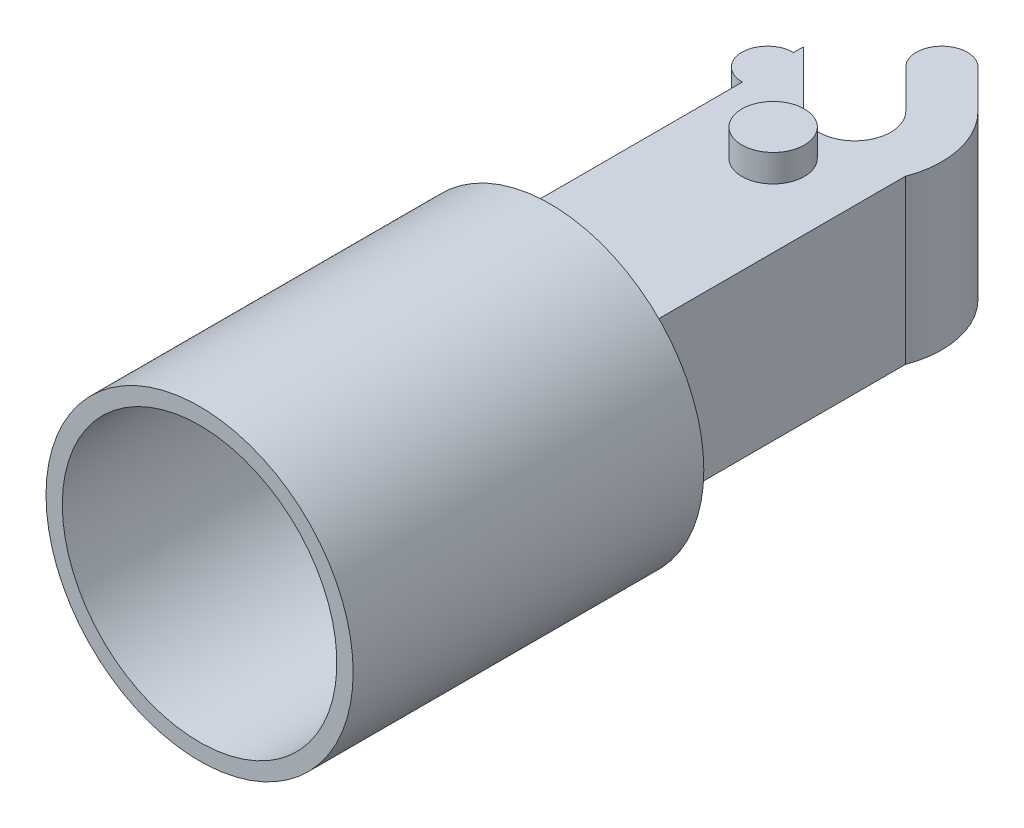
SolidWorks part; units mm, degrees
material "6063-T5"
ref_plane "Front Plane" through (0, 0, 0) normal (0, 0, 1) x (1, 0, 0)
ref_plane "Top Plane" through (0, 0, 0) normal (0, 1, 0) x (1, 0, 0)
ref_plane "Right Plane" through (0, 0, 0) normal (1, 0, 0) x (0, 0, -1)
sketch "Sketch1" plane through (0, 0, 0) normal (0, 1, 0) x (1, 0, 0)
  circle A0 centre (0, 0) radius 2.875
  dimension "D1" = 5.75
extrude "Boss-Extrude1" add sketch "Sketch1" along normal blind 20
ref_plane "Plane4" through (0, 2.5, 0) normal (0, -1, 0) x (-1, 0, 0)
sketch "Sketch2" plane through (0, 2.5, 0) normal (0, -1, 0) x (-1, 0, 0)
  line L0 (-7.5, 0) -> (-7.5, 10)
  line L1 (7.5, 10) -> (7.5, 0)
  line L2 (-4, 0) -> (-4, 10)
  line L3 (4, 0) -> (4, 10)
  line L4 (-7.5, 10) -> (-4, 10)
  line L5 (4, 10) -> (7.5, 10)
  line L6 (7.5, 0) -> (4, 0)
  circle A0 centre (0, 0) radius 7.5
  circle A1 centre (0, 0) radius 4
  circle A2 centre (-5.75, 10) radius 1.75
  circle A3 centre (5.75, 10) radius 1.75
  circle A4 centre (0, 0) radius 2.875
  circle A5 centre (0, 7.5) radius 4
  dimension "D1" = 15
  dimension "D3" = 10
  dimension "D4" = 5.75
  dimension "D2" = 10
extrude "Boss-Extrude2" add sketch "Sketch2" against normal blind 14.99
sketch "Sketch3" plane through (0, 2.5, 0) normal (0, -1, 0) x (-1, 0, 0)
  line L0 (7.5, 0) -> (7.5, -20.5)
  line L1 (-7.5, 0) -> (-7.5, -20.5)
  line L2 (-7.5, -20.5) -> (7.5, -20.5)
  arc A0 (7.5, 0) -> (-7.5, 0) centre (0, 0) cw
  dimension "D1" = 20.5
  dimension "D2" = 20.5
extrude "Boss-Extrude3" add sketch "Sketch3" against normal up to surface (14.99 mm away) up to face at (0, 17.49, -5.875)
sketch "Sketch4" plane through (0, 0, 20.5) normal (0, 0, 1) x (1, 0, 0)
  line L0 (-7.5, 9.995) -> (7.5, 9.995)
  line L1 (-7.5, 17.49) -> (-7.5, 2.5) construction
  line L2 (7.5, 17.49) -> (7.5, 2.5) construction
  circle A0 centre (0, 9.995) radius 14.125
  line M1 (7.5, 17.49) -> (-7.5, 17.49)
  line M2 (-7.5, 17.49) -> (-7.5, 2.5)
  line M3 (-7.5, 2.5) -> (7.5, 2.5)
  line M4 (7.5, 2.5) -> (7.5, 17.49)
  dimension "D1" = 28.25
extrude "Boss-Extrude4" add sketch "Sketch4" along normal blind 6.25 contours A0 M1 M4 M3 M2 | L0 M2 M4 M1 | L0 M2 M3 M4
sketch "Sketch5" plane through (0, 0, 26.75) normal (0, 0, 1) x (1, 0, 0)
  circle A0 centre (0, 9.995) radius 14.125
  circle A1 centre (0, 9.995) radius 12.625
  dimension "D1" = 28.25
  dimension "D2" = 25.25
extrude "Boss-Extrude5" add sketch "Sketch5" along normal blind 26
sketch "Sketch6" plane through (0, 2.5, 0) normal (0, -1, 0) x (-1, 0, 0)
  line L0 (-4.01, 11.51) -> (-5.671, 13.171)
  line L1 (-8.02, 7.5) -> (0, 15.52)
  line L2 (0, 15.52) -> (8.02, 7.5)
  line L3 (8.02, 7.5) -> (0, -0.52)
  line L4 (0, -0.52) -> (-8.02, 7.5)
  line L5 (-5.671, 13.171) -> (-2.1354, 16.7065)
  line L6 (-4.01, 11.51) -> (-2.349, 9.849)
  line L7 (-2.349, 9.849) -> (1.1865, 13.3845)
  line L8 (-2.1354, 16.7065) -> (1.1865, 13.3845)
  line L9 (4.01, 3.49) -> (5.671, 1.829)
  line L10 (5.671, 1.829) -> (9.2065, 5.3646)
  line L11 (4.01, 3.49) -> (2.349, 5.151)
  line L12 (2.349, 5.151) -> (5.8845, 8.6865)
  line L13 (5.8845, 8.6865) -> (9.2065, 5.3646)
  circle A1 centre (0, 7.5) radius 8.02
  circle A2 centre (-4.01, 11.51) radius 2.349
  circle A4 centre (4.01, 3.49) radius 2.349
  circle A5 centre (0, 7.5) radius 3.322
  circle A6 centre (-0.4745, 15.0455) radius 2.349
  circle A8 centre (7.5455, 7.0255) radius 2.35
  arc M15 (4, 7.5) -> (-4, 7.5) centre (0, 7.5) cw
  line M16 (-4, 7.5) -> (-4, 10)
  arc M17 (-4, 10) -> (-7.5, 10) centre (-5.75, 10) ccw
  line M18 (-7.5, 10) -> (-7.5, -20.5)
  line M20 (7.5, -20.5) -> (7.5, 10)
  circle M22 centre (0, 0) radius 2.875
  dimension "D5" = 4.7
  dimension "D1" = 5
  dimension "D2" = 5
  dimension "D3" = 5
  dimension "D4" = 5
extrude "Boss-Extrude8" add sketch "Sketch6" against normal up to surface (14.99 mm away) contours A6 L5 A1 | A6 A1 A2 L1 | A6 L1 A2 L7 | A2 A1 M17 | A2 L1 M17 M18 | A4 A2 L1 L4 L3 M15 M16 M18 M22 | A5 A2 A4 M16 M15 | A1 L1 M17 M18 | L4 L1 M18 | L4 A1 M18 | A1 L4 M18 M22 | A8 L12 A4 L3 M15 | A8 L3 A4 A1 M20 | A4 L3 A1 M22 | L4 L3 M22 | L3 A1 M22 | A1 L4 M22 | A4 L12 M15
sketch "Sketch7" plane through (0, 2.5, 0) normal (0, -1, 0) x (-1, 0, 0)
  line L1 (3.9245, 6.7265) -> (1.0238, 9.6273)
  line L2 (1.0238, 9.6273) -> (6.7778, 15.3813)
  line L5 (3.9245, 6.7265) -> (9.6477, 12.4497)
  line L6 (9.6477, 12.4497) -> (6.7778, 15.3813)
extrude "Cut-Extrude3" cut sketch "Sketch7" against normal through all
ref_plane "Plane6" through (3.75, 0, -3.75) normal (0.7071, 0, -0.7071) x (-0.7071, 0, -0.7071)
ref_plane "Plane5" through (3.75, 0, -3.75) normal (0.7071, 0, -0.7071) x (-0.7071, 0, -0.7071)
